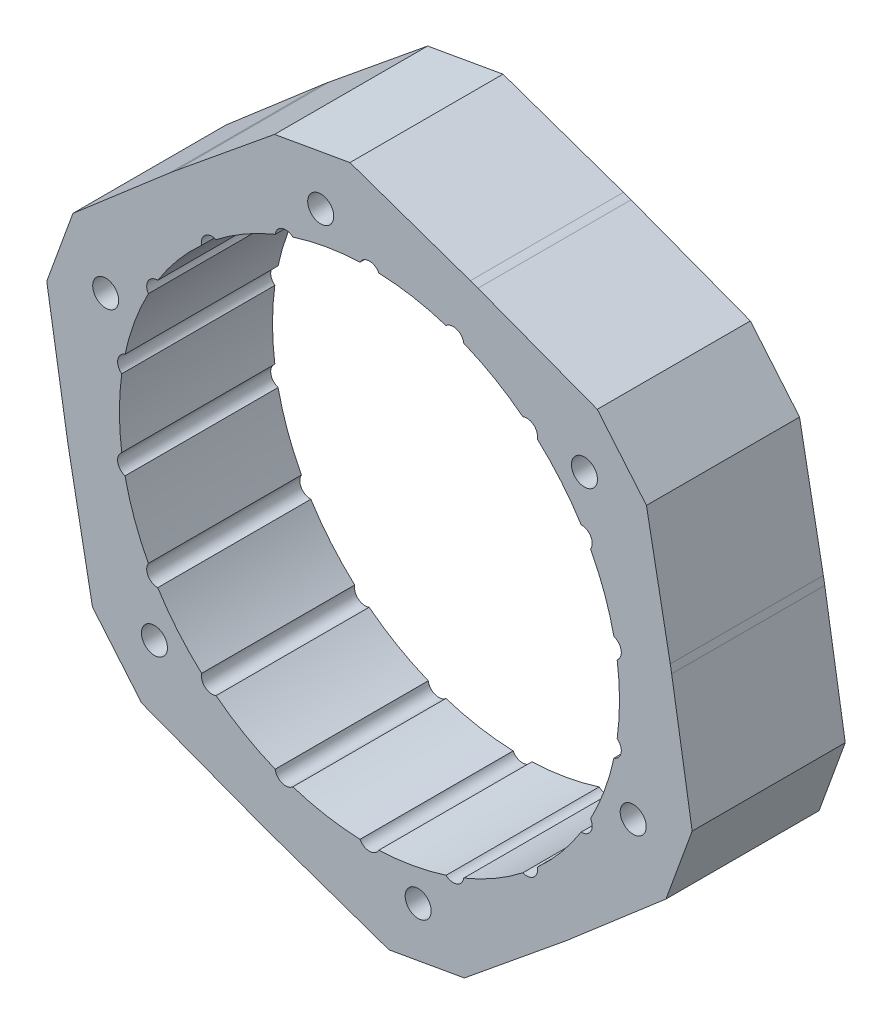
SolidWorks part; units mm, degrees
ref_plane "Front Plane" through (0, 0, 0) normal (0, 0, 1) x (1, 0, 0)
ref_plane "Top Plane" through (0, 0, 0) normal (0, 1, 0) x (1, 0, 0)
ref_plane "Right Plane" through (0, 0, 0) normal (1, 0, 0) x (0, 0, -1)
sketch "Sketch1" plane through (0, 0, 0) normal (0, 0, 1) x (1, 0, 0)
  line L0 (-16.417, 45.1052) -> (0, 0) construction
  line L1 (0, 0) -> (-8.3351, 47.2708) construction
  circle A2 centre (0, 0) radius 60
  arc A36 (-15.0158, 46.6425) -> (-18.4784, 45.3822) centre (-16.417, 45.1052) ccw
  arc A40 (-32.8857, 36.3254) -> (-41.484, 26.0783) centre (0, 0) ccw
  arc A42 (-2.0783, 47.9149) -> (-14.435, 45.7361) centre (0, 0) ccw construction
  arc A58 (-18.4784, 45.3822) -> (-30.0629, 38.6939) centre (0, 0) ccw
  arc A59 (-1.8424, 48.9653) -> (-15.0158, 46.6425) centre (0, 0) ccw
  circle A60 centre (0, 0) radius 48 construction
  arc A61 (1.8424, 48.9653) -> (-1.8424, 48.9653) centre (0, 48) ccw
  arc A62 (14.435, 45.7361) -> (2.0783, 47.915) centre (0, 0) ccw construction
  arc A63 (18.4784, 45.3822) -> (15.0158, 46.6425) centre (16.417, 45.1052) ccw
  arc A64 (29.2071, 38.0409) -> (18.3408, 44.3145) centre (0, 0) ccw construction
  arc A65 (32.8857, 36.3254) -> (30.0629, 38.6939) centre (30.8538, 36.7701) ccw
  arc A66 (40.4564, 25.7573) -> (32.3912, 35.3691) centre (0, 0) ccw construction
  arc A67 (43.3264, 22.8871) -> (41.484, 26.0783) centre (41.5692, 24) ccw
  arc A68 (46.8261, 10.367) -> (42.5347, 22.1576) centre (0, 0) ccw construction
  arc A69 (48.5414, 6.6883) -> (47.9015, 10.3172) centre (47.2708, 8.3351) ccw
  arc A70 (47.5479, -6.2737) -> (47.5479, 6.2737) centre (0, 0) ccw construction
  arc A71 (47.9015, -10.3172) -> (48.5414, -6.6883) centre (47.2708, -8.3351) ccw
  arc A72 (42.5347, -22.1576) -> (46.8261, -10.367) centre (0, 0) ccw construction
  arc A73 (41.484, -26.0783) -> (43.3264, -22.8871) centre (41.5692, -24) ccw
  arc A74 (32.3912, -35.3691) -> (40.4564, -25.7573) centre (0, 0) ccw construction
  arc A75 (30.0629, -38.6939) -> (32.8857, -36.3254) centre (30.8538, -36.7701) ccw
  arc A76 (18.3408, -44.3145) -> (29.2071, -38.0409) centre (0, 0) ccw construction
  arc A77 (15.0158, -46.6425) -> (18.4784, -45.3822) centre (16.417, -45.1052) ccw
  arc A78 (2.0783, -47.9149) -> (14.435, -45.7361) centre (0, 0) ccw construction
  arc A79 (-1.8424, -48.9654) -> (1.8424, -48.9654) centre (0, -48) ccw
  arc A80 (-14.435, -45.7361) -> (-2.0783, -47.9149) centre (0, 0) ccw construction
  arc A81 (-18.4784, -45.3822) -> (-15.0158, -46.6425) centre (-16.417, -45.1052) ccw
  arc A82 (-29.2071, -38.0409) -> (-18.3408, -44.3145) centre (0, 0) ccw construction
  arc A83 (-32.8857, -36.3254) -> (-30.0629, -38.6939) centre (-30.8538, -36.7701) ccw
  arc A84 (-40.4564, -25.7573) -> (-32.3912, -35.3691) centre (0, 0) ccw construction
  arc A85 (-43.3264, -22.8871) -> (-41.484, -26.0783) centre (-41.5692, -24) ccw
  arc A86 (-46.8261, -10.367) -> (-42.5347, -22.1576) centre (0, 0) ccw construction
  arc A87 (-48.5414, -6.6883) -> (-47.9015, -10.3172) centre (-47.2708, -8.3351) ccw
  arc A88 (-47.5479, 6.2737) -> (-47.5479, -6.2737) centre (0, 0) ccw construction
  arc A89 (-47.9015, 10.3172) -> (-48.5414, 6.6883) centre (-47.2708, 8.3351) ccw
  arc A90 (-42.5347, 22.1576) -> (-46.8261, 10.367) centre (0, 0) ccw construction
  arc A91 (-41.484, 26.0783) -> (-43.3264, 22.8871) centre (-41.5692, 24) ccw
  arc A92 (-32.3912, 35.3691) -> (-40.4564, 25.7573) centre (0, 0) ccw construction
  arc A93 (-30.0629, 38.6939) -> (-32.8857, 36.3254) centre (-30.8538, 36.7701) ccw
  arc A94 (-18.3408, 44.3145) -> (-29.2071, 38.0409) centre (0, 0) ccw construction
  arc A95 (15.0158, 46.6425) -> (1.8424, 48.9653) centre (0, 0) ccw
  arc A96 (30.0629, 38.6939) -> (18.4784, 45.3822) centre (0, 0) ccw
  arc A97 (41.484, 26.0783) -> (32.8857, 36.3254) centre (0, 0) ccw
  arc A98 (47.9015, 10.3172) -> (43.3264, 22.8871) centre (0, 0) ccw
  arc A99 (48.5414, -6.6883) -> (48.5414, 6.6883) centre (0, 0) ccw
  arc A100 (43.3264, -22.8871) -> (47.9015, -10.3172) centre (0, 0) ccw
  arc A101 (32.8857, -36.3254) -> (41.484, -26.0783) centre (0, 0) ccw
  arc A102 (18.4784, -45.3822) -> (30.0629, -38.6939) centre (0, 0) ccw
  arc A103 (1.8424, -48.9654) -> (15.0158, -46.6425) centre (0, 0) ccw
  arc A104 (-15.0158, -46.6425) -> (-1.8424, -48.9654) centre (0, 0) ccw
  arc A105 (-30.0629, -38.6939) -> (-18.4784, -45.3822) centre (0, 0) ccw
  arc A106 (-41.484, -26.0783) -> (-32.8857, -36.3254) centre (0, 0) ccw
  arc A107 (-47.9015, -10.3172) -> (-43.3264, -22.8871) centre (0, 0) ccw
  arc A108 (-48.5414, 6.6883) -> (-48.5414, -6.6883) centre (0, 0) ccw
  arc A109 (-43.3264, 22.8871) -> (-47.9015, 10.3172) centre (0, 0) ccw
  point P59 (0, 0)
  point P85 (0, 0)
  dimension "D1" = 2.08
  dimension "D2" = 47.96
  dimension "D3" = 120
  dimension "D6" = 98
  dimension "D5" = 18
  dimension "D4" = 10
extrude "Boss-Extrude1" add sketch "Sketch1" along normal blind 30
sketch "Sketch2" plane through (0, 0, 30) normal (0, 0, 1) x (1, 0, 0)
  line L0 (0, 0) -> (0, 60) construction
  line L1 (0, 0) -> (-9.5506, 54.1644) construction
  circle A0 centre (0, 0) radius 55 construction
  circle A1 centre (-9.5506, 54.1644) radius 2.55
  circle A2 centre (0, 0) radius 60 construction
  circle A3 centre (42.1324, 35.3533) radius 2.55
  circle A4 centre (51.6831, -18.8111) radius 2.55
  circle A5 centre (9.5506, -54.1644) radius 2.55
  circle A6 centre (-42.1324, -35.3533) radius 2.55
  circle A7 centre (-51.6831, 18.8111) radius 2.55
  point P22 (0, 0)
  dimension "D1" = 110
  dimension "D2" = 5.1
  dimension "D3" = 10
  dimension "D4" = 6
extrude "Cut-Extrude2" cut sketch "Sketch2" against normal through all
sketch "Sketch3" plane through (0, 0, 30) normal (0, 0, 1) x (1, 0, 0)
  line L0 (0, 0) -> (-9.5506, 54.1644) construction
  line L1 (-9.5506, 54.1644) -> (-11.2871, 64.0125) construction
  line L2 (0, 65) -> (0, 0) construction
  line L3 (-37.9588, 46.4664) -> (-18.5978, 62.2826)
  line L4 (-18.5978, 62.2826) -> (-3.8257, 64.8873)
  line L5 (-3.8257, 64.8873) -> (19.7772, 56.6468)
  line L6 (54.2812, 35.7568) -> (58.9462, 11.1959)
  line L7 (44.6394, 47.2475) -> (54.2812, 35.7568)
  line L8 (21.2617, 56.1065) -> (44.6394, 47.2475)
  line L9 (58.1069, -29.1305) -> (39.169, -45.4509)
  line L10 (63.2372, -15.0351) -> (58.1069, -29.1305)
  line L11 (59.2205, 9.6401) -> (63.2372, -15.0351)
  line L12 (3.8257, -64.8873) -> (-19.7772, -56.6468)
  line L13 (18.5978, -62.2826) -> (3.8257, -64.8873)
  line L14 (37.9588, -46.4664) -> (18.5978, -62.2826)
  line L15 (-54.2812, -35.7568) -> (-58.9462, -11.1959)
  line L16 (-44.6394, -47.2475) -> (-54.2812, -35.7568)
  line L17 (-21.2617, -56.1065) -> (-44.6394, -47.2475)
  line L18 (-58.1069, 29.1305) -> (-39.169, 45.4509)
  line L19 (-63.2372, 15.0351) -> (-58.1069, 29.1305)
  line L20 (-59.2205, -9.6401) -> (-63.2372, 15.0351)
  circle A0 centre (0, 0) radius 65 construction
  circle A1 centre (0, 0) radius 60 construction
  arc A2 (-37.9588, 46.4664) -> (19.7772, 56.6468) centre (0, 0) cw
  arc A3 (21.2617, 56.1065) -> (58.9462, 11.1959) centre (0, 0) cw
  arc A4 (59.2205, 9.6401) -> (39.169, -45.4509) centre (0, 0) cw
  arc A5 (37.9588, -46.4664) -> (-19.7772, -56.6468) centre (0, 0) cw
  arc A6 (-21.2617, -56.1065) -> (-58.9462, -11.1959) centre (0, 0) cw
  arc A7 (-59.2205, -9.6401) -> (-39.169, 45.4509) centre (0, 0) cw
  point P11 (-11.2117, 63.585)
  point P38 (0, 0)
  dimension "D1" = 130
  dimension "D2" = 15
  dimension "D3" = 6
extrude "Boss-Extrude2" add sketch "Sketch3" against normal blind 30
